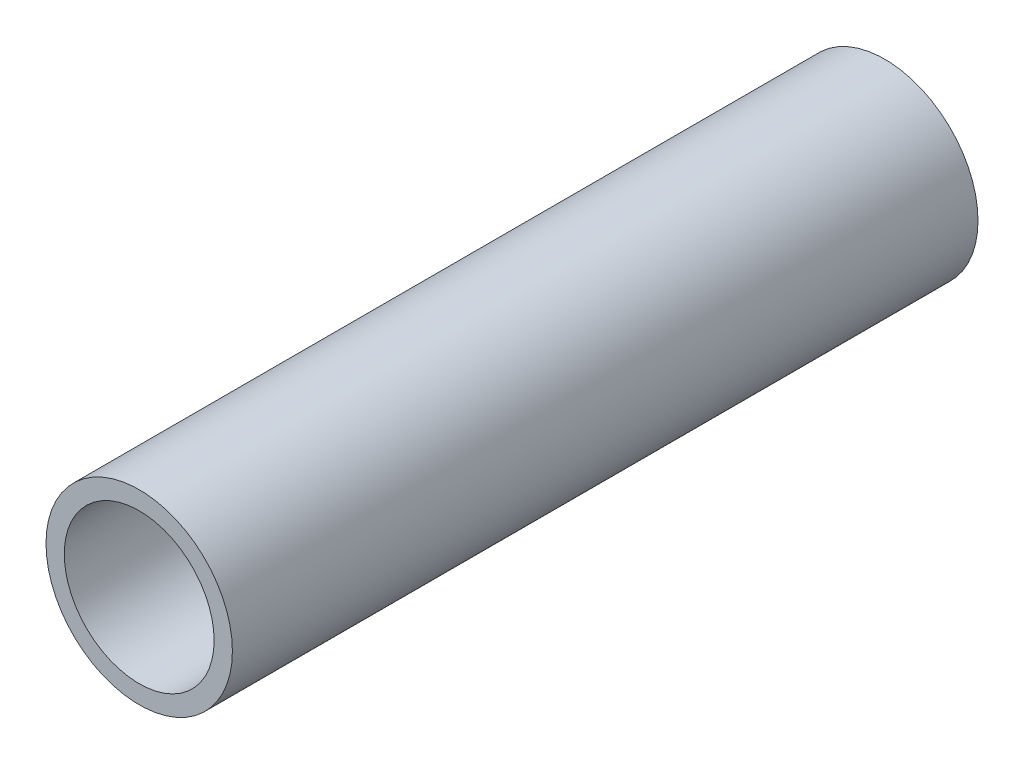
SolidWorks part; units mm, degrees
material "6061-T6 (SS)"
ref_plane "Front Plane" through (0, 0, 0) normal (0, 0, 1) x (1, 0, 0)
ref_plane "Top Plane" through (0, 0, 0) normal (0, 1, 0) x (1, 0, 0)
ref_plane "Right Plane" through (0, 0, 0) normal (1, 0, 0) x (0, 0, -1)
sketch "Sketch2" plane through (0, 0, 0) normal (0, 0, 1) x (1, 0, 0)
  circle A0 centre (0, 0) radius 6.35
  circle A1 centre (0, 0) radius 5.1054
  dimension "D1" = 12.7
  dimension "D2" = 10.2108
extrude "Boss-Extrude1" add sketch "Sketch2" along normal blind 50.8
